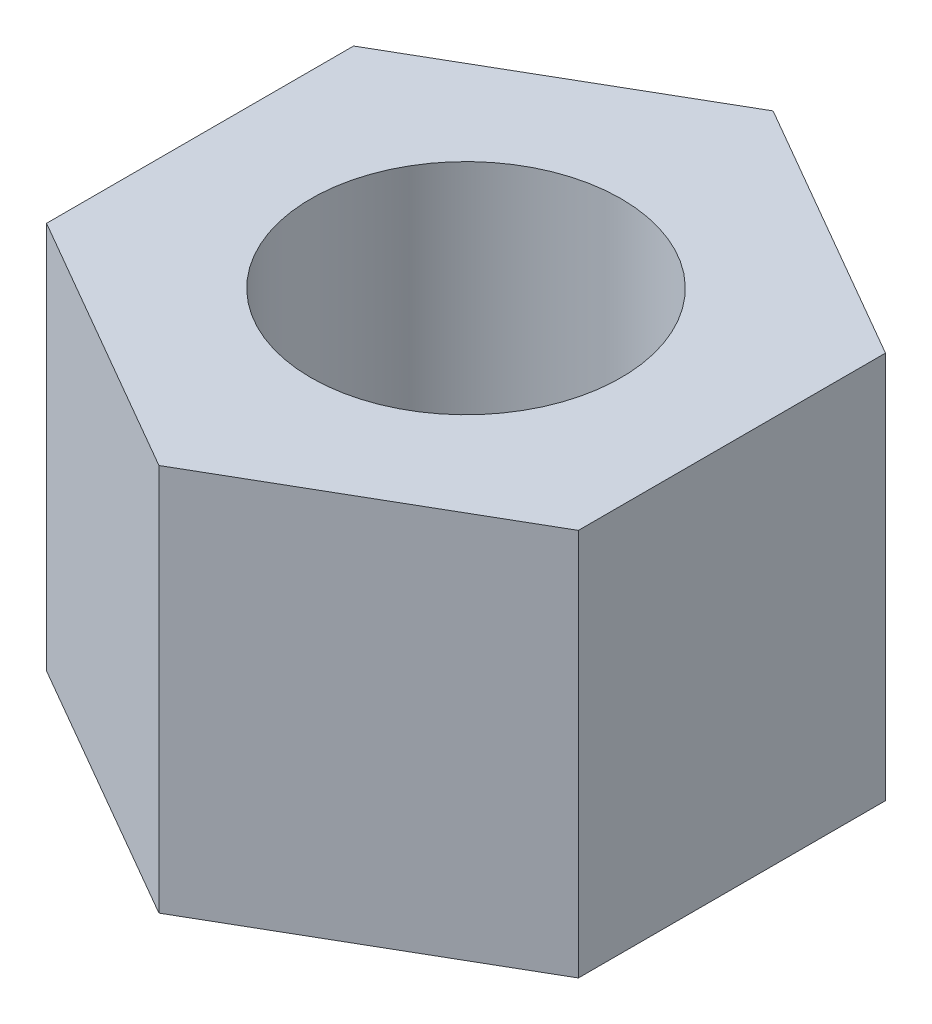
SolidWorks part; units mm, degrees
ref_plane "Спереди" through (0, 0, 0) normal (0, 0, 1) x (1, 0, 0)
ref_plane "Сверху" through (0, 0, 0) normal (0, 1, 0) x (1, 0, 0)
ref_plane "Справа" through (0, 0, 0) normal (1, 0, 0) x (0, 0, -1)
sketch "Эскиз1" plane through (0, 0, 0) normal (0, 1, 0) x (1, 0, 0)
  line L1 (0, -3.9606) -> (3.43, -1.9803)
  line L2 (3.43, -1.9803) -> (3.43, 1.9803)
  line L3 (3.43, 1.9803) -> (0, 3.9606)
  line L4 (0, 3.9606) -> (-3.43, 1.9803)
  line L5 (-3.43, 1.9803) -> (-3.43, -1.9803)
  line L6 (-3.43, -1.9803) -> (0, -3.9606)
  circle A0 centre (0, 0) radius 3.43 construction
  circle A1 centre (0, 0) radius 2
extrude "Вытянуть1" add sketch "Эскиз1" along normal blind 5
